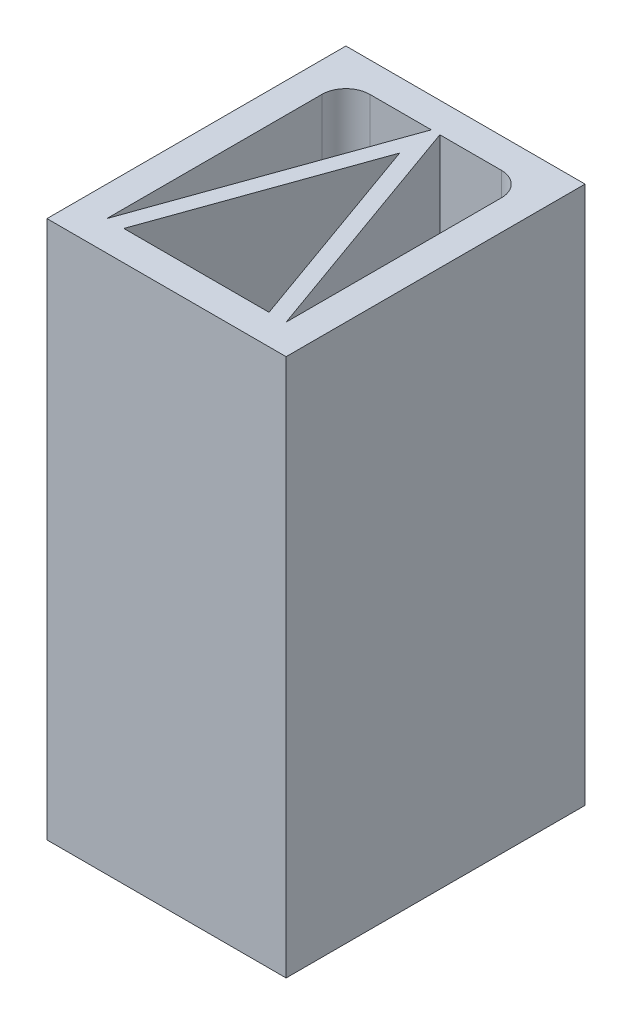
SolidWorks part; units mm, degrees
ref_plane "Front Plane" through (0, 0, 0) normal (0, 0, 1) x (1, 0, 0)
ref_plane "Top Plane" through (0, 0, 0) normal (0, 1, 0) x (1, 0, 0)
ref_plane "Right Plane" through (0, 0, 0) normal (1, 0, 0) x (0, 0, -1)
sketch "Sketch1" plane through (0, 0, 0) normal (0, 1, 0) x (1, 0, 0)
  line L0 (10, 25) -> (10, 22.5) construction
  line L1 (0, 0) -> (20, 0)
  line L2 (0, 0) -> (0, 25)
  line L3 (0, 25) -> (20, 25)
  line L4 (20, 0) -> (20, 25)
  line L5 (2.5, 22.5) -> (17.5, 22.5)
  line L6 (2.5, 22.5) -> (2.5, 2.5)
  line L7 (2.5, 2.5) -> (17.5, 2.5)
  line L8 (17.5, 22.5) -> (17.5, 2.5)
  line L9 (0, 12.5) -> (2.5, 12.5) construction
  dimension "D1" = 20
  dimension "D2" = 25
  dimension "D3" = 2.5
  dimension "D4" = 2.5
extrude "Boss-Extrude1" add sketch "Sketch1" along normal blind 45
sketch "Sketch3" plane through (0, 0, 0) normal (0, -1, 0) x (1, 0, 0)
  line L0 (17.5, -2.5) -> (10, -23.5)
  line L2 (10, -23.5) -> (2.5, -2.5)
  line L3 (10, -23.5) -> (10, -2.5) construction
  line L4 (2.5, -2.5) -> (17.5, -2.5) construction
  line L5 (17.5, -2.5) -> (16.0714, -2.5)
  line L6 (16.0714, -2.5) -> (10, -19.5)
  line L7 (10, -19.5) -> (3.9286, -2.5)
  line L8 (3.9286, -2.5) -> (2.5, -2.5)
  line L9 (17.5, -22.5) -> (2.5, -22.5) construction
  dimension "D1" = 4
  dimension "D2" = 1
extrude "Boss-Extrude4" add sketch "Sketch3" against normal through all
fillet "Fillet2" radius 2 2 edges at (2.5, 22.5, -22.5) (17.5, 22.5, -22.5)
